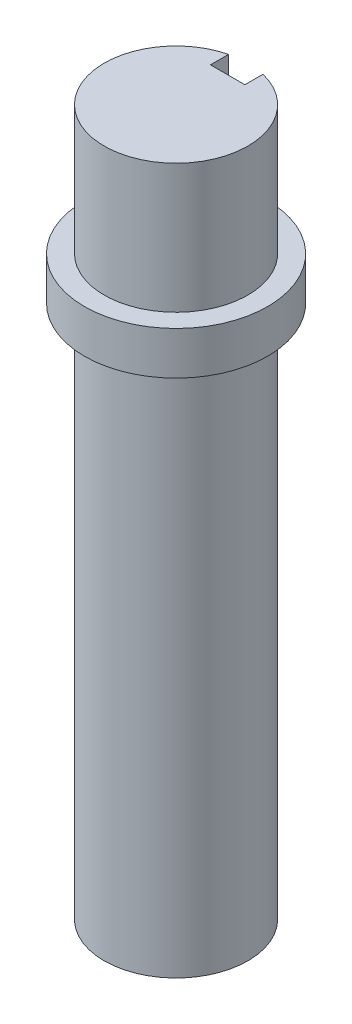
SolidWorks part; units mm, degrees
ref_plane "Front Plane" through (0, 0, 0) normal (0, 0, 1) x (1, 0, 0)
ref_plane "Top Plane" through (0, 0, 0) normal (0, 1, 0) x (1, 0, 0)
ref_plane "Right Plane" through (0, 0, 0) normal (1, 0, 0) x (0, 0, -1)
sketch "Sketch1" plane through (0, 0, 0) normal (0, 1, 0) x (1, 0, 0)
  circle A0 centre (0, 0) radius 8.35
  dimension "D1" = 16.7
extrude "Boss-Extrude1" add sketch "Sketch1" along normal blind 82
ref_plane "Plane1" through (0, 62, 0) normal (0, 1, 0) x (1, 0, 0)
sketch "Sketch2" plane through (0, 62, 0) normal (0, 1, 0) x (1, 0, 0)
  circle A0 centre (0, 0) radius 10.65
  dimension "D1" = 21.3
extrude "Boss-Extrude2" add sketch "Sketch2" along normal blind 5
sketch "Sketch3" plane through (0, 82, 0) normal (0, 1, 0) x (1, 0, 0)
  line L1 (2, 6) -> (-2, 6)
  line L2 (2, 6) -> (2, 14.4426)
  line L3 (2, 14.4426) -> (-2, 14.4426)
  line L4 (-2, 6) -> (-2, 14.4426)
  point P4 (0, 6)
  dimension "D1" = 6
  dimension "D2" = 4
extrude "Cut-Extrude1" cut sketch "Sketch3" against normal up to surface (15 mm away) up to face at (0, 67, 8.35)
